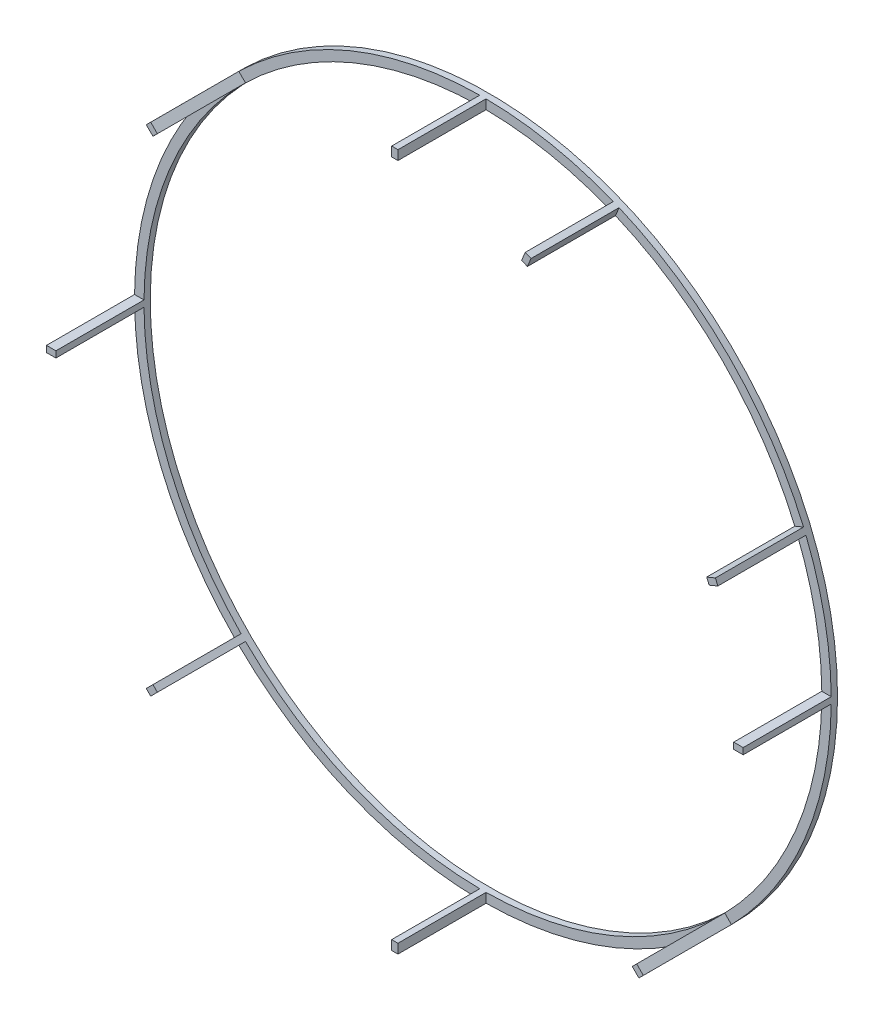
SolidWorks part; units mm, degrees
material "PLA"
ref_plane "Front Plane" through (0, 0, 0) normal (0, 0, 1) x (1, 0, 0)
ref_plane "Top Plane" through (0, 0, 0) normal (0, 1, 0) x (1, 0, 0)
ref_plane "Right Plane" through (0, 0, 0) normal (1, 0, 0) x (0, 0, -1)
sketch "Sketch1" plane through (0, 0, 0) normal (0, 0, 1) x (1, 0, 0)
  line L2 (3.5358, 69.9509) -> (3.5358, 69.9591)
  line L3 (-3.5358, 69.9526) -> (-3.5358, 69.9591)
  line L8 (-3.5358, -69.9509) -> (-3.5358, -69.9591)
  line L9 (3.5358, -69.9526) -> (3.5358, -69.9591)
  line L13 (-69.9384, -3.5358) -> (-69.9591, -3.5358)
  circle A3 centre (0, 0) radius 107.7318
  circle A22 centre (0, 0) radius 110.7318
  point P76 (0, 0)
  point P93 (0, 0)
  point P118 (0, 0)
  dimension "D7" = 3
extrude "Boss-Extrude1" add sketch "Sketch1" along normal blind 2 separate body
sketch "Sketch3" plane through (0, 0, 0) normal (0, 0, 1) x (1, 0, 0)
  line L0 (0, 107.7318) -> (0, 110.7318) construction
  line L3 (0, 107.7318) -> (0, 110.7318) construction
  line L4 (1, 107.7272) -> (1, 110.7273)
  line L5 (-1, 107.7272) -> (-1, 110.7273)
  line L8 (107.7272, 1) -> (110.7273, 1)
  line L9 (107.7272, -1) -> (110.7273, -1)
  line L10 (76.8817, -75.4675) -> (79.0031, -77.5889)
  line L11 (75.4675, -76.8817) -> (77.5889, -79.0031)
  line L12 (1, -107.7272) -> (1, -110.7273)
  line L13 (-1, -107.7272) -> (-1, -110.7273)
  line L14 (-75.4675, -76.8817) -> (-77.5889, -79.0031)
  line L15 (-76.8817, -75.4675) -> (-79.0031, -77.5889)
  line L16 (-107.7272, -1) -> (-110.7273, -1)
  line L17 (-107.7272, 1) -> (-110.7273, 1)
  line L18 (-76.8817, 75.4675) -> (-79.0031, 77.5889)
  line L19 (-75.4675, 76.8817) -> (-77.5889, 79.0031)
  line L20 (75.4675, 76.8817) -> (77.5889, 79.0031) [skipped]
  line L21 (76.8817, 75.4675) -> (79.0031, 77.5889) [skipped]
  line L22 (0, 0) -> (76.1779, 76.1779) construction
  line L23 (0, 0) -> (99.5312, 41.2272) construction
  line L24 (0, 0) -> (119.7649, 0) construction
  line L25 (0, 0) -> (105.6618, 21.0174) construction
  line L26 (99.1442, 42.1493) -> (101.916, 43.2974)
  line L27 (99.9096, 40.3015) -> (102.6814, 41.4496)
  line L28 (0, 0) -> (41.2272, 99.5312) construction
  line L29 (40.3015, 99.9096) -> (41.4496, 102.6814)
  line L30 (42.1493, 99.1442) -> (43.2974, 101.916)
  circle A3 centre (0, 0) radius 110.7318 construction
  arc A4 (1, 110.7273) -> (-1, 110.7273) centre (0, 0) ccw
  circle A5 centre (0, 0) radius 107.7318 construction
  arc A6 (1, 107.7272) -> (-1, 107.7272) centre (0, 0) ccw
  arc A7 (110.7273, -1) -> (110.7273, 1) centre (0, 0) ccw
  arc A8 (107.7272, -1) -> (107.7272, 1) centre (0, 0) ccw
  arc A9 (77.5889, -79.0031) -> (79.0031, -77.5889) centre (0, 0) ccw
  arc A10 (75.4675, -76.8817) -> (76.8817, -75.4675) centre (0, 0) ccw
  arc A11 (-1, -110.7273) -> (1, -110.7273) centre (0, 0) ccw
  arc A12 (-1, -107.7272) -> (1, -107.7272) centre (0, 0) ccw
  arc A13 (-79.0031, -77.5889) -> (-77.5889, -79.0031) centre (0, 0) ccw
  arc A14 (-76.8817, -75.4675) -> (-75.4675, -76.8817) centre (0, 0) ccw
  arc A15 (-110.7273, 1) -> (-110.7273, -1) centre (0, 0) ccw
  arc A16 (-107.7272, 1) -> (-107.7272, -1) centre (0, 0) ccw
  arc A17 (-77.5889, 79.0031) -> (-79.0031, 77.5889) centre (0, 0) ccw
  arc A18 (-75.4675, 76.8817) -> (-76.8817, 75.4675) centre (0, 0) ccw
  arc A19 (79.0031, 77.5889) -> (77.5889, 79.0031) centre (0, 0) ccw [skipped]
  arc A20 (76.8817, 75.4675) -> (75.4675, 76.8817) centre (0, 0) ccw [skipped]
  arc A22 (99.1442, 42.1493) -> (99.9096, 40.3015) centre (0, 0) cw
  arc A23 (101.916, 43.2974) -> (102.6814, 41.4496) centre (0, 0) cw
  arc A24 (43.2974, 101.916) -> (41.4496, 102.6814) centre (0, 0) ccw
  arc A25 (42.1493, 99.1442) -> (40.3015, 99.9096) centre (0, 0) ccw
  point P2 (1, 114.3965)
  point P42 (0, 0)
  dimension "D1" = 1
  dimension "D3" = 22.5
  dimension "D4" = 11.25
  dimension "D5" = 45
  dimension "D2" = 8
extrude "Boss-Extrude3" add sketch "Sketch3" along normal blind 30
